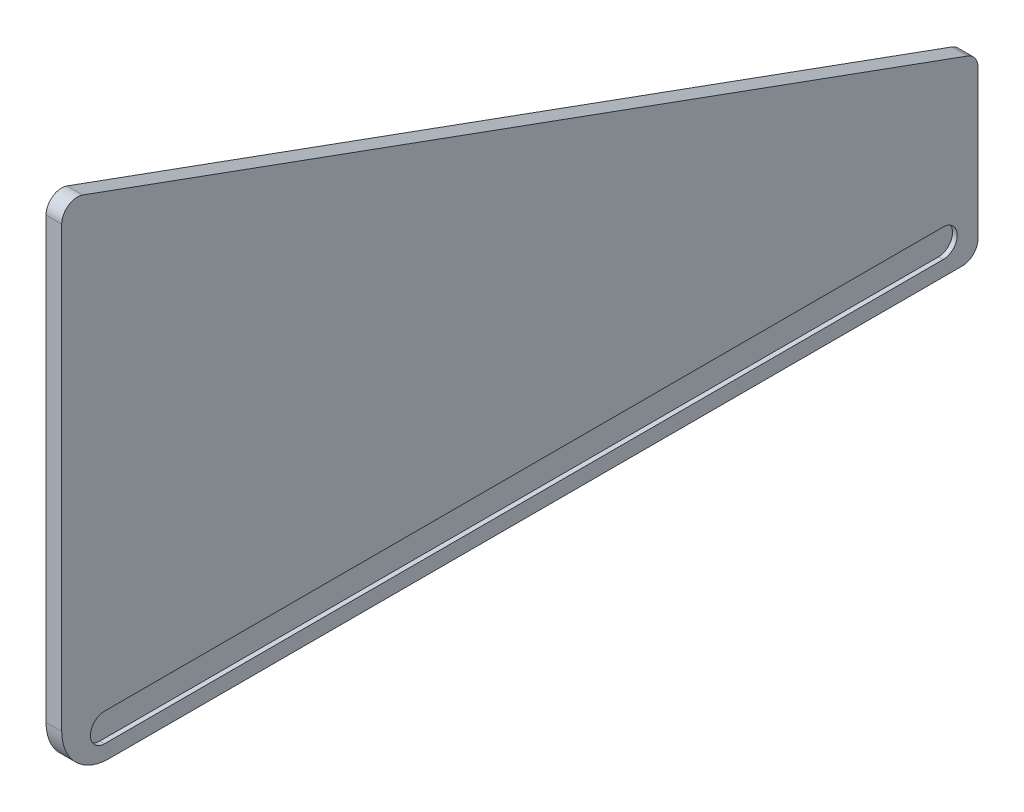
SolidWorks part; units mm, degrees
material "Hexcel AS4C (3000 Filaments)"
ref_plane "Front Plane" through (0, 0, 0) normal (0, 0, 1) x (1, 0, 0)
ref_plane "Top Plane" through (0, 0, 0) normal (0, 1, 0) x (1, 0, 0)
ref_plane "Right Plane" through (0, 0, 0) normal (1, 0, 0) x (0, 0, -1)
sketch "Sketch1" plane through (0, 0, 0) normal (1, 0, 0) x (0, 0, -1)
  line L0 (0, -14.2815) -> (0, -294.2815)
  line L1 (0, 29.2892) -> (0, -29.2892) construction
  line L2 (30, -324.2815) -> (573.8156, -324.2815)
  line L3 (583.8156, -314.2815) -> (583.8156, -219.4936)
  line L4 (577.2358, -210.0966) -> (13.4202, -4.8846)
  arc A0 (30, -324.2815) -> (0, -294.2815) centre (30, -294.2815) cw
  arc A1 (573.8156, -324.2815) -> (583.8156, -314.2815) centre (573.8156, -314.2815) ccw
  arc A2 (583.8156, -219.4936) -> (577.2358, -210.0966) centre (573.8156, -219.4936) ccw
  arc A3 (13.4202, -4.8846) -> (0, -14.2815) centre (10, -14.2815) ccw
  point P9 (0, -324.2815)
  point P16 (0, 0)
  dimension "D2" = 30
  dimension "D3" = 10
  dimension "D1" = 70
  dimension "D4" = 280
  dimension "D5" = 600
extrude "Boss-Extrude1" add sketch "Sketch1" along normal blind 10
sketch "Sketch2" plane through (10, 0, 0) normal (1, 0, 0) x (0, 0, -1)
  arc A0 (23.1622, -218.0173) -> (26.7381, -200.3183) centre (26.5742, -209.4959) cw
  arc A1 (549.474, -291.831) -> (546.1549, -257.731) centre (546.1581, -274.9423) ccw
  arc A2 (26.9502, -47.7372) -> (35.1249, -39.1544) centre (32.8168, -45.1404) cw
  arc A3 (356.3201, -205.3163) -> (353.1695, -171.1817) centre (353.1695, -188.3944) ccw
  spline S0 degree 3 poles (23.1622, -218.0173) (143.0808, -266.0342) (284.6699, -324.5722) (474.7501, -306.5023) (549.474, -291.831) knots 0 0 0 0 0.576112 1 1 1 1
  spline S1 degree 3 poles (26.7381, -200.3183) (45.9144, -200.6608) (151.3211, -255.5104) (414.8803, -286.3851) (542.4311, -257.7317) (546.1549, -257.731) knots 0 0 0 0 0.560935 0.660935 1 1 1 1
  spline S2 degree 3 poles (26.9502, -47.7372) (35.3127, -66.6296) (121.3965, -217.9891) (352.8389, -205.9644) (356.3201, -205.3163) knots 0 0 0 0 0.590315 1 1 1 1
  spline S3 degree 3 poles (35.1249, -39.1544) (50.603, -45.1224) (99.0425, -170.6619) (331.224, -171.1817) (353.1695, -171.1817) knots 0 0 0 0 0.639196 1 1 1 1
sketch "Sketch3" plane through (0, 0, 0) normal (-1, 0, 0) x (0, 0, 1)
  arc A2 (-23.1622, -218.0173) -> (-26.7381, -200.3183) centre (-26.5742, -209.4959) ccw
  arc A3 (-546.1549, -257.731) -> (-549.474, -291.831) centre (-546.1581, -274.9423) ccw
  arc A4 (-23.1622, -218.0173) -> (-26.7381, -200.3183) centre (-26.5742, -209.4959) ccw
  arc A5 (-546.1549, -257.731) -> (-549.474, -291.831) centre (-546.1581, -274.9423) ccw
  arc A6 (-26.9502, -47.7372) -> (-35.1249, -39.1544) centre (-32.8168, -45.1404) ccw
  arc A7 (-353.1695, -171.1817) -> (-356.3201, -205.3163) centre (-353.1695, -188.3944) ccw
  arc A8 (-26.9502, -47.7372) -> (-35.1249, -39.1544) centre (-32.8168, -45.1404) ccw
  arc A9 (-353.1695, -171.1817) -> (-356.3201, -205.3163) centre (-353.1695, -188.3944) ccw
  spline S2 degree 3 poles (-1816.3187, -2605.5409) (75.9737, 231.5319) (247.8188, -208.7531) (-624.0722, -310.8909) (-1042.2542, -16.1976) (2292.0508, -1228.213) knots -1.514422 -1.514422 -1.514422 -1.514422 0.560935 0.660935 1.793718 1.793718 1.793718 1.793718 only from (-26.7381, -200.3183) to (-546.1549, -257.731)
  spline S3 degree 3 poles (2381.1668, -869.8797) (-1836.6269, 336.9299) (-160.0228, -831.4717) (182.4388, 107.8527) (2926.7447, 268.4202) knots -2.671816 -2.671816 -2.671816 -2.671816 0.423888 2.573484 2.573484 2.573484 2.573484 only from (-549.474, -291.831) to (-23.1622, -218.0173)
  spline S4 degree 3 poles (-26.7381, -200.3183) (-45.9144, -200.6608) (-151.3211, -255.5104) (-414.8803, -286.3851) (-542.4311, -257.7317) (-546.1549, -257.731) knots 0 0 0 0 0.560935 0.660935 1 1 1 1
  spline S5 degree 3 poles (-549.474, -291.831) (-474.7501, -306.5023) (-284.6699, -324.5722) (-143.0808, -266.0342) (-23.1622, -218.0173) knots 0 0 0 0 0.423888 1 1 1 1
  spline S6 degree 3 poles (620.0267, -2965.5435) (-330.0266, 628.3163) (484.1929, -482.6485) (-970.471, -49.8454) (2628.5866, -498.6084) knots -1.524676 -1.524676 -1.524676 -1.524676 0.639196 1.989327 1.989327 1.989327 1.989327 only from (-35.1249, -39.1544) to (-353.1695, -171.1817)
  spline S7 degree 3 poles (2605.5885, -677.7833) (-930.4728, -32.6201) (328.2216, -605.2679) (-87.5838, 704.2328) (-600.8148, -2989.1172) knots -0.959059 -0.959059 -0.959059 -0.959059 0.409685 2.43502 2.43502 2.43502 2.43502 only from (-356.3201, -205.3163) to (-26.9502, -47.7372)
  spline S8 degree 3 poles (-35.1249, -39.1544) (-50.603, -45.1224) (-99.0425, -170.6619) (-331.224, -171.1817) (-353.1695, -171.1817) knots 0 0 0 0 0.639196 1 1 1 1
  spline S9 degree 3 poles (-356.3201, -205.3163) (-352.8389, -205.9644) (-121.3965, -217.9891) (-35.3127, -66.6296) (-26.9502, -47.7372) knots 0 0 0 0 0.409685 1 1 1 1
  dimension "D1" = 0
  dimension "D2" = 0
sketch "Sketch4" plane through (0, 0, 0) normal (-1, 0, 0) x (0, 0, 1)
  line L0 (-561.5873, -305.6301) -> (-27.292, -305.6301) construction
  line L1 (-561.5873, -296.6301) -> (-27.292, -296.6301)
  line L2 (-561.5873, -314.6301) -> (-27.292, -314.6301)
  arc A0 (-561.5873, -296.6301) -> (-561.5873, -314.6301) centre (-561.5873, -305.6301) ccw
  arc A1 (-27.292, -314.6301) -> (-27.292, -296.6301) centre (-27.292, -305.6301) ccw
  point P2 (-294.4396, -305.6301)
  dimension "D1" = 18
extrude "Cut-Extrude4" cut sketch "Sketch3" against normal blind 3
sketch "Sketch5" plane through (10, 0, 0) normal (1, 0, 0) x (0, 0, -1)
  line L2 (561.5873, -296.6301) -> (27.292, -296.6301)
  line L3 (27.292, -314.6301) -> (561.5873, -314.6301)
  line L4 (561.5873, -296.6301) -> (27.292, -296.6301)
  line L5 (27.292, -314.6301) -> (561.5873, -314.6301)
  arc A2 (27.292, -296.6301) -> (27.292, -314.6301) centre (27.292, -305.6301) ccw
  arc A3 (561.5873, -314.6301) -> (561.5873, -296.6301) centre (561.5873, -305.6301) ccw
  arc A4 (27.292, -296.6301) -> (27.292, -314.6301) centre (27.292, -305.6301) ccw
  arc A5 (561.5873, -314.6301) -> (561.5873, -296.6301) centre (561.5873, -305.6301) ccw
  dimension "D1" = 0
extrude "Cut-Extrude5" cut sketch "Sketch5" against normal blind 3
